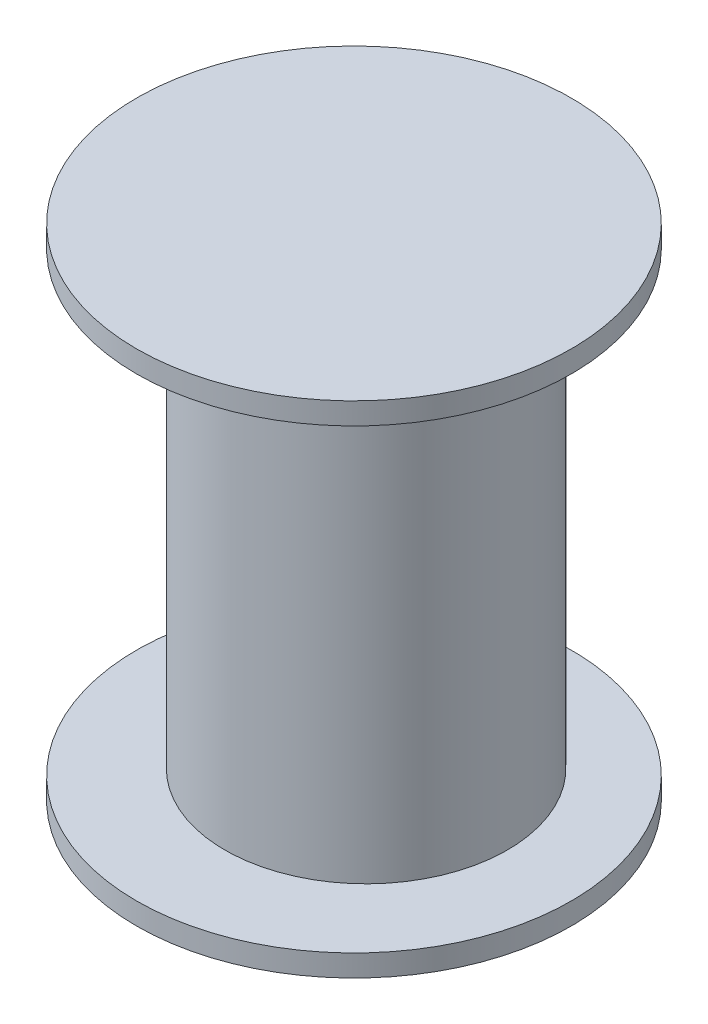
SolidWorks part; units mm, degrees
ref_plane "Alzado" through (0, 0, 0) normal (0, 0, 1) x (1, 0, 0)
ref_plane "Planta" through (0, 0, 0) normal (0, 1, 0) x (1, 0, 0)
ref_plane "Vista lateral" through (0, 0, 0) normal (1, 0, 0) x (0, 0, -1)
sketch "Croquis1" plane through (0, 0, 0) normal (0, 1, 0) x (1, 0, 0)
  circle A0 centre (0, 0) radius 10
extrude "Saliente-Extruir1" add sketch "Croquis1" along normal blind 1
sketch "Croquis2" plane through (0, 1, 0) normal (0, 1, 0) x (1, 0, 0)
  circle A0 centre (0, 0.5594) radius 6.5
extrude "Saliente-Extruir2" add sketch "Croquis2" along normal blind 21
sketch "Croquis3" plane through (0, 22, 0) normal (0, 1, 0) x (1, 0, 0)
  circle A0 centre (0, 0) radius 10
extrude "Saliente-Extruir3" add sketch "Croquis3" along normal blind 1
